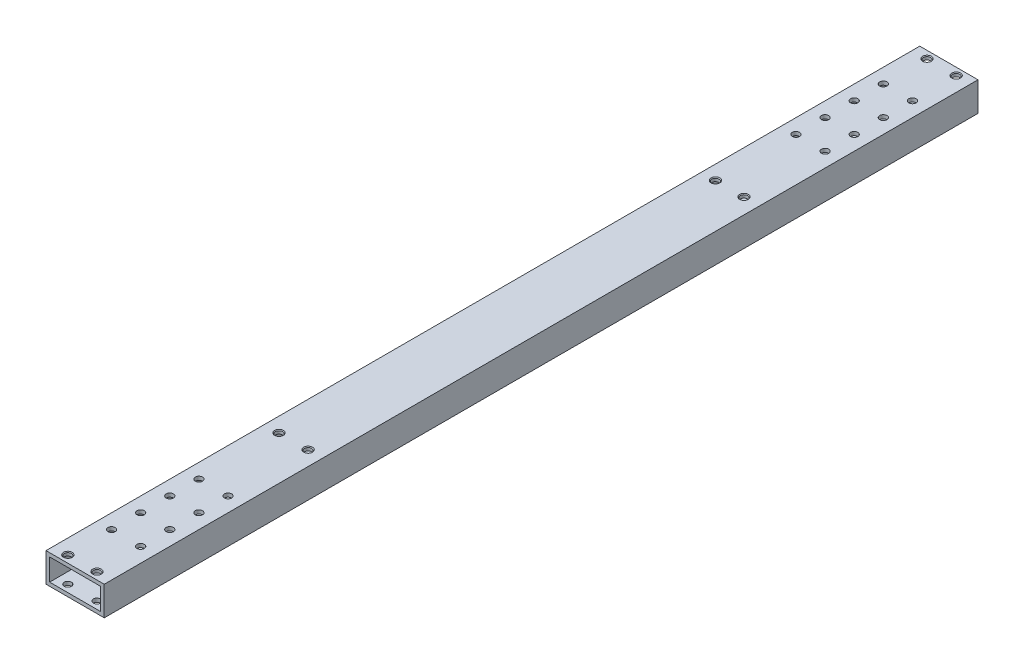
SolidWorks part; units mm, degrees
ref_plane "Front Plane" through (0, 0, 0) normal (0, 0, 1) x (1, 0, 0)
ref_plane "Top Plane" through (0, 0, 0) normal (0, 1, 0) x (1, 0, 0)
ref_plane "Right Plane" through (0, 0, 0) normal (1, 0, 0) x (0, 0, -1)
sketch "Sketch1" plane through (0, 0, 0) normal (0, 0, 1) x (1, 0, 0)
  line L0 (3.175, 3.175) -> (47.625, 3.175)
  line L1 (0, 0) -> (50.8, 0)
  line L2 (0, 0) -> (0, 25.4)
  line L3 (0, 25.4) -> (50.8, 25.4)
  line L4 (50.8, 0) -> (50.8, 25.4)
  line L5 (47.625, 3.175) -> (47.625, 22.225)
  line L6 (3.175, 22.225) -> (47.625, 22.225)
  line L7 (3.175, 3.175) -> (3.175, 22.225)
  dimension "D1" = 25.4
  dimension "D2" = 50.8
  dimension "D3" = 3.175
extrude "Boss-Extrude1" add sketch "Sketch1" along normal blind 762
sketch "Sketch4" plane through (0, 25.4, 0) normal (0, 1, 0) x (1, 0, 0)
  line L0 (50.8, -762) -> (50.8, 0) construction
  line L1 (50.8, 0) -> (0, 0) construction
  point P0 (12.7, -6.35)
  point P2 (38.1, -6.35)
  point P4 (12.3399, -190.5)
  point P6 (37.1905, -190.5)
  dimension "D1" = 25.4
  dimension "D2" = 12.7
  dimension "D3" = 6.35
  dimension "D4" = 6.35
  dimension "D5" = 190.5
  dimension "D6" = 190.5
hole_wizard "1/4 (0.25) Diameter Hole1" positions "Sketch4" profile "Sketch3" hole size "1/4" standard "ANSI Inch" end condition through all
sketch "Sketch3" plane through (12.7, 25.4, 6.35) normal (1, 0, 0) x (0, 0, 1)
  line L0 (0, 0) -> (0, 25.4)
  line L1 (0, 25.4) -> (3.175, 25.4)
  line L2 (3.175, 25.4) -> (3.175, 0.635)
  line L3 (3.175, 0.635) -> (3.81, 0)
  line L5 (3.81, 0) -> (0, 0)
  line L6 (-3.175, 0.635) -> (-3.81, 0) construction
  line L11 (0, -6.35) -> (0, 107.95) construction
  dimension "Thru Hole Dia." = 6.35
  dimension "Thru Hole Depth" = 25.4
  dimension "Near C'Sink Dia." = 7.62
  dimension "Near C'Sink Angle" = 90
sketch "Sketch7" plane through (0, 25.4, 0) normal (0, 1, 0) x (1, 0, 0)
  line L0 (50.8, -762) -> (50.8, 0) construction
  line L1 (0, -762) -> (0, 0) construction
  line L2 (50.8, -762) -> (0, -762) construction
  point P0 (12.7, -755.65)
  point P2 (38.1, -755.65)
  point P4 (38.1, -571.5)
  point P6 (12.7, -571.5)
  dimension "D1" = 25.4
  dimension "D2" = 12.7
  dimension "D3" = 12.7
  dimension "D4" = 12.7
  dimension "D5" = 6.35
  dimension "D6" = 190.5
  dimension "D7" = 190.5
hole_wizard "1/4 (0.25) Diameter Hole2" positions "Sketch7" profile "Sketch6" hole size "1/4" standard "ANSI Inch" end condition through all
sketch "Sketch6" plane through (12.7, 25.4, 755.65) normal (1, 0, 0) x (0, 0, 1)
  line L0 (0, 0) -> (0, 25.4)
  line L1 (0, 25.4) -> (3.175, 25.4)
  line L2 (3.175, 25.4) -> (3.175, 0.635)
  line L3 (3.175, 0.635) -> (3.81, 0)
  line L5 (3.81, 0) -> (0, 0)
  line L6 (-3.175, 0.635) -> (-3.81, 0) construction
  line L11 (0, -6.35) -> (0, 107.95) construction
  dimension "Thru Hole Dia." = 6.35
  dimension "Thru Hole Depth" = 25.4
  dimension "Near C'Sink Dia." = 7.62
  dimension "Near C'Sink Angle" = 90
sketch "Sketch9" plane through (0, 25.4, 0) normal (0, 1, 0) x (1, 0, 0)
  line L0 (0, -381) -> (50.8, -381) construction
  line L1 (12.7, -6.35) -> (38.1, -6.35) construction
  line L2 (12.7, -6.35) -> (12.7, -95.25) construction
  line L3 (12.7, -95.25) -> (38.1, -95.25) construction
  line L4 (38.1, -6.35) -> (38.1, -95.25) construction
  line L9 (0, -762) -> (0, 0) construction
  line L10 (50.8, -762) -> (50.8, 0) construction
  line L11 (12.7, -95.25) -> (12.7, -120.65) construction
  line L12 (38.1, -95.25) -> (38.1, -120.65) construction
  line L13 (38.1, -120.65) -> (12.7, -120.65) construction
  circle A0 centre (12.7, -95.25) radius 3.175
  circle A1 centre (38.1, -95.25) radius 3.175
  circle A4 centre (12.7, -69.85) radius 3.175
  circle A5 centre (38.1, -69.85) radius 3.175
  circle A6 centre (12.7, -44.45) radius 3.175
  circle A7 centre (38.1, -44.45) radius 3.175
  circle A8 centre (38.1, -120.65) radius 3.175
  circle A9 centre (12.7, -120.65) radius 3.175
  circle A10 centre (12.7, -641.35) radius 3.175
  circle A11 centre (38.1, -641.35) radius 3.175
  circle A12 centre (38.1, -666.75) radius 3.175
  circle A13 centre (12.7, -666.75) radius 3.175
  circle A14 centre (12.7, -692.15) radius 3.175
  circle A15 centre (38.1, -692.15) radius 3.175
  circle A16 centre (38.1, -717.55) radius 3.175
  circle A17 centre (12.7, -717.55) radius 3.175
  dimension "D3" = 6.35
  dimension "D1" = 88.9
  dimension "D2" = 3
  dimension "D4" = 25.4
  dimension "D6" = 25.4
extrude "Cut-Extrude1" cut sketch "Sketch9" against normal through all both and the other way through all
